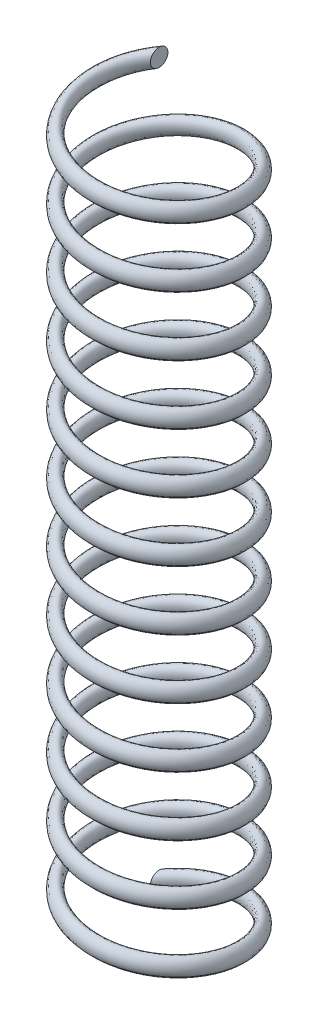
SolidWorks part; units mm, degrees
ref_plane "Front Plane" through (0, 0, 0) normal (0, 0, 1) x (1, 0, 0)
ref_plane "Top Plane" through (0, 0, 0) normal (0, 1, 0) x (1, 0, 0)
ref_plane "Right Plane" through (0, 0, 0) normal (1, 0, 0) x (0, 0, -1)
sketch "Sketch1" plane through (0, 0, 0) normal (0, 1, 0) x (1, 0, 0)
  circle A0 centre (0, 0) radius 12.5
curve "Helix/Spiral1" pitch 10.1667 height 122 turns 12
ref_plane "Plane1" through (-8.8388, 0, 0) normal (1, 0, 0) x (0, 0, -1)
sketch "Sketch2" plane through (-8.8388, 0, 0) normal (1, 0, 0) x (0, 0, -1)
  circle A0 centre (8.8679, 0) radius 1.5
sweep "Sweep1" add profiles "Sketch2" path "Helix/Spiral1"
sketch "Sketch3" plane through (0, 0, 0) normal (0, 1, 0) x (1, 0, 0)
  circle A0 centre (0, 0) radius 11.5
